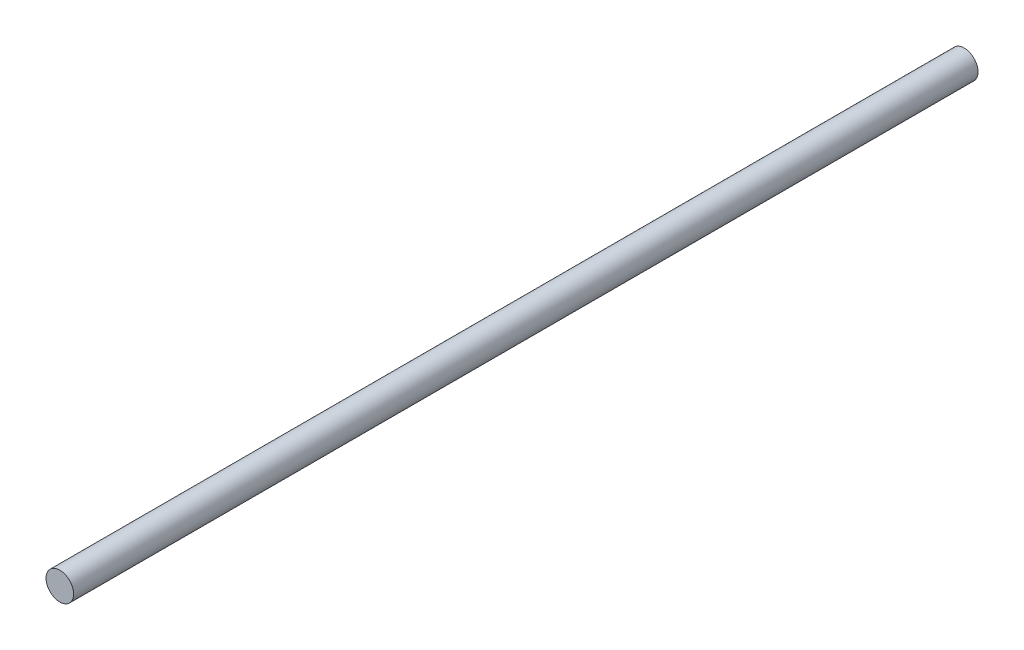
SolidWorks part; units mm, degrees
ref_plane "Front Plane" through (0, 0, 0) normal (0, 0, 1) x (1, 0, 0)
ref_plane "Top Plane" through (0, 0, 0) normal (0, 1, 0) x (1, 0, 0)
ref_plane "Right Plane" through (0, 0, 0) normal (1, 0, 0) x (0, 0, -1)
sketch "Sketch1" plane through (0, 0, 0) normal (0, 0, 1) x (1, 0, 0)
  circle A0 centre (0, 0) radius 6.35
  dimension "D1" = 12.7
extrude "Boss-Extrude1" add sketch "Sketch1" along normal blind 415.925
